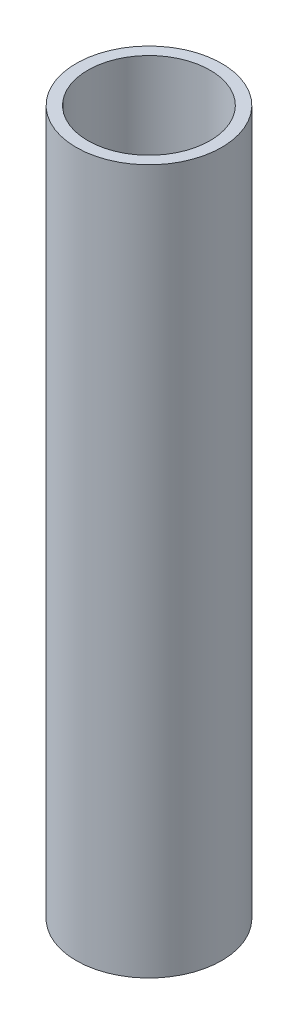
SolidWorks part; units mm, degrees
ref_plane "Front Plane" through (0, 0, 0) normal (0, 0, 1) x (1, 0, 0)
ref_plane "Top Plane" through (0, 0, 0) normal (0, 1, 0) x (1, 0, 0)
ref_plane "Right Plane" through (0, 0, 0) normal (1, 0, 0) x (0, 0, -1)
sketch "Sketch1" plane through (0, 0, 0) normal (0, 1, 0) x (1, 0, 0)
  circle A0 centre (0, 0) radius 12.5
  circle A1 centre (0, 0) radius 10.5
  dimension "D1" = 25
  dimension "D2" = 21
extrude "Boss-Extrude1" add sketch "Sketch1" along normal blind 121
equation "\"D1@Sketch1\" = \"cf_tube_outer_diameter\""
equation "\"D1@Boss-Extrude1\"= \"mid_tube_length\""
equation "\"cf_tube_outer_diameter\"= 25mm"
equation "\"mid_plate_mid_to_top\" = 100mm"
equation "\"mid_plate_mid_to_bottom\" = 30mm"
equation "\"mid_plate_horizontal_spacing\"=250mm"
equation "\"mid_tube_length\" = 121mm"
equation "\"cf_tube_inner_diameter\" = 21mm"
equation "\"D2@Sketch1\"=\"cf_tube_inner_diameter\""
